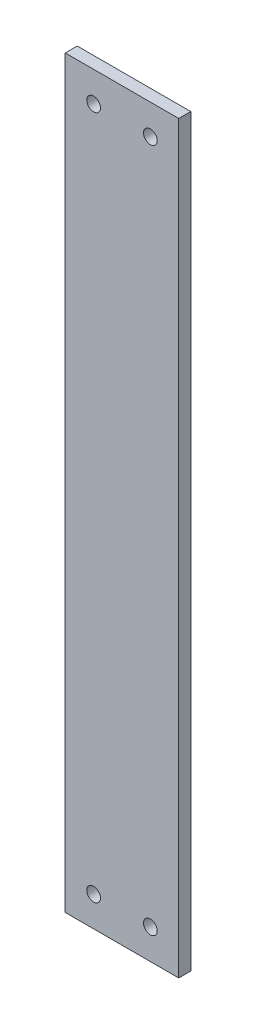
SolidWorks part; units mm, degrees
ref_plane "Plan de face" through (0, 0, 0) normal (0, 0, 1) x (1, 0, 0)
ref_plane "Plan de dessus" through (0, 0, 0) normal (0, 1, 0) x (1, 0, 0)
ref_plane "Plan de droite" through (0, 0, 0) normal (1, 0, 0) x (0, 0, -1)
sketch "Esquisse1" plane through (0, 0, 0) normal (0, 0, 1) x (1, 0, 0)
  line L0 (0, 46.3512) -> (0, -64.121) construction
  line L1 (-76.7381, 0) -> (96.6776, 0) construction
  line L3 (17, 112.5) -> (-17, 112.5) construction
  line L4 (17, 112.5) -> (17, -112.5) construction
  line L5 (17, -112.5) -> (-17, -112.5) construction
  line L6 (-17, 112.5) -> (-17, -112.5) construction
  line L7 (17, 112.5) -> (-17, -112.5) construction
  line L8 (17, -112.5) -> (-17, 112.5) construction
  line L9 (17, -111.5) -> (-17, -111.5)
  line L10 (17, -111.5) -> (17, 111.5)
  line L11 (17, 111.5) -> (-17, 111.5)
  line L12 (-17, -111.5) -> (-17, 111.5)
  line L13 (17, -111.5) -> (-17, 111.5) construction
  line L14 (17, 111.5) -> (-17, -111.5) construction
  circle A0 centre (-8.5, 102.5) radius 2.05
  circle A5 centre (-8.5, -102.5) radius 2.05
  circle A6 centre (8.5, -102.5) radius 2.05
  circle A7 centre (8.5, 102.5) radius 2.05
  point P1 (0, 0)
  point P10 (0, 0)
  point P15 (7.5, -102.5)
  point P17 (7.5, -89.3534)
  point P23 (-37.3612, -93.035)
  point P26 (0, 0)
  dimension "D1" = 17
  dimension "D8" = 4.1
  dimension "D3" = 34
  dimension "D4" = 225
  dimension "D5" = 223
  dimension "D6" = 34
  dimension "D7" = 10
extrude "Boss.-Extru.1" add sketch "Esquisse1" along normal blind 3.6
